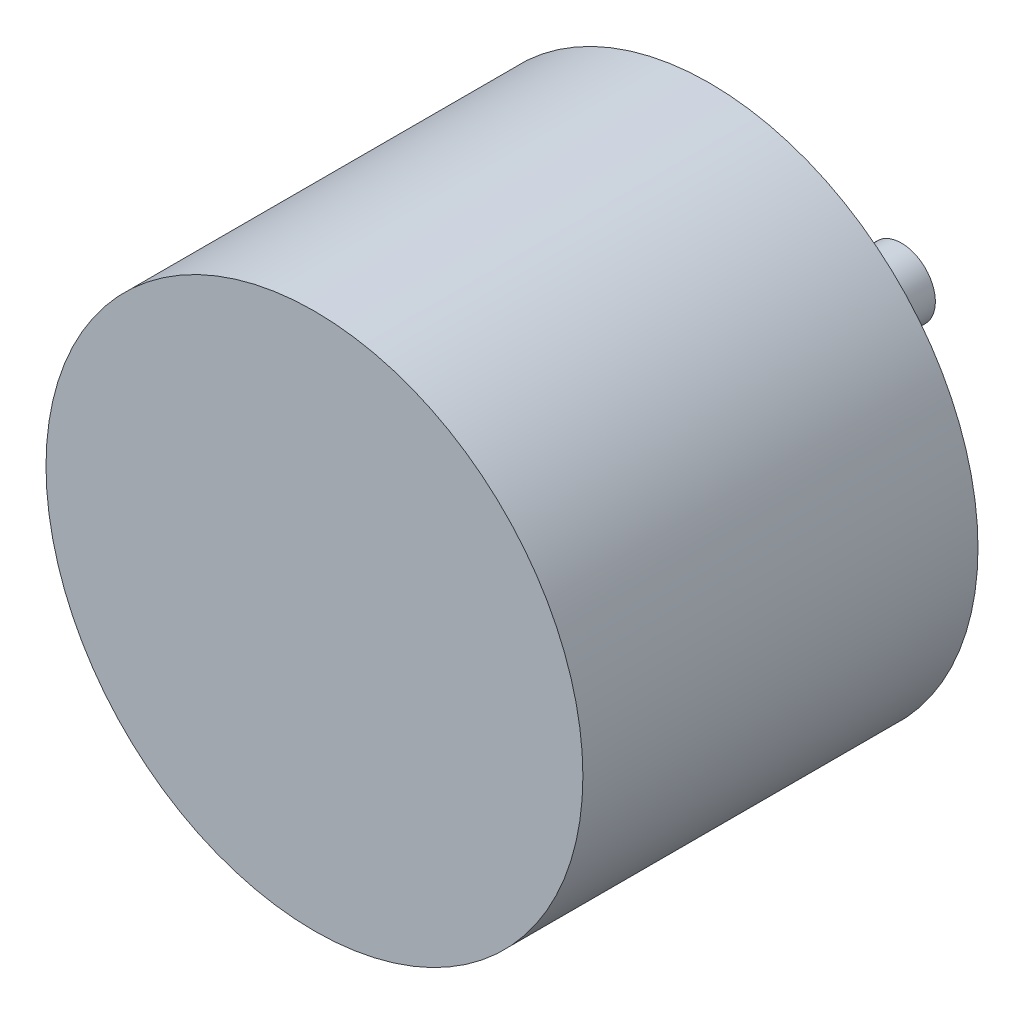
SolidWorks part; units mm, degrees
ref_plane "Front Plane" through (0, 0, 0) normal (0, 0, 1) x (1, 0, 0)
ref_plane "Top Plane" through (0, 0, 0) normal (0, 1, 0) x (1, 0, 0)
ref_plane "Right Plane" through (0, 0, 0) normal (1, 0, 0) x (0, 0, -1)
sketch "Sketch1" plane through (0, 0, 0) normal (0, 1, 0) x (1, 0, 0)
  line L0 (-36.903, 63.1163) -> (-36.903, -22.0472) construction
  line L1 (-36.903, -9.6328) -> (-13.123, -9.6328)
  line L2 (-13.123, -9.6328) -> (-13.123, 25.3672)
  line L3 (-13.123, 25.3672) -> (-26.903, 25.3672)
  line L4 (-26.903, 25.3672) -> (-26.903, 29.3672)
  line L5 (-26.903, 29.3672) -> (-33.903, 29.3672)
  line L6 (-33.903, 29.3672) -> (-33.903, 42.3672)
  line L7 (-33.903, 42.3672) -> (-36.903, 42.3672)
  line L8 (-36.903, -9.6328) -> (-36.903, 42.3672)
  dimension "D1" = 3
  dimension "D2" = 7
  dimension "D3" = 23.78
  dimension "D4" = 35
  dimension "D5" = 4
  dimension "D6" = 13
revolve "Revolve1" add sketch "Sketch1" angle 360 about L0
sketch "Sketch2" plane through (0, 0, -25.3672) normal (0, 0, -1) x (-1, 0, 0)
  line L5 (25.403, -11.5) -> (48.403, 11.5) construction
  line L6 (25.403, 11.5) -> (48.403, -11.5) construction
  circle A0 centre (25.403, 11.5) radius 2
  circle A1 centre (48.403, 11.5) radius 2
  circle A2 centre (48.403, -11.5) radius 2
  circle A3 centre (25.403, -11.5) radius 2
  point P0 (36.903, 0)
  dimension "D1" = 23
  dimension "D2" = 23
extrude "Cut-Extrude1" cut sketch "Sketch2" against normal blind 10
